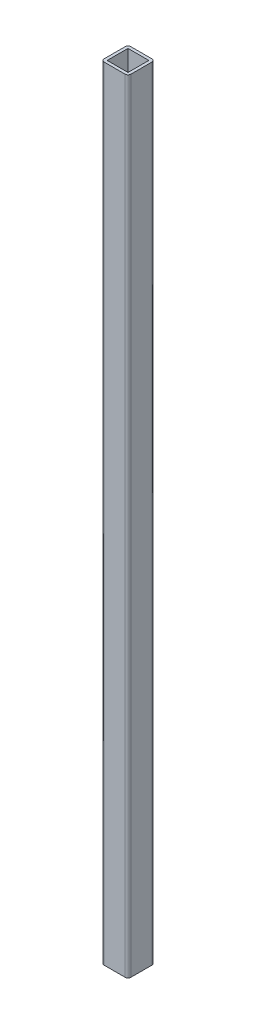
SolidWorks part; units mm, degrees
material "Plain Carbon Steel"
ref_plane "Front Plane" through (0, 0, 0) normal (0, 0, 1) x (1, 0, 0)
ref_plane "Top Plane" through (0, 0, 0) normal (0, 1, 0) x (1, 0, 0)
ref_plane "Right Plane" through (0, 0, 0) normal (1, 0, 0) x (0, 0, -1)
sketch "Sketch1" plane through (0, 0, 0) normal (0, 1, 0) x (1, 0, 0)
  line L1 (2.8, 0) -> (22.8, 0)
  line L2 (0, -2.8) -> (0, -22.8)
  line L3 (2.8, -25.6) -> (22.8, -25.6)
  line L4 (25.6, -2.8) -> (25.6, -22.8)
  arc A0 (22.8, 0) -> (25.6, -2.8) centre (22.8, -2.8) cw
  arc A1 (22.8, -25.6) -> (25.6, -22.8) centre (22.8, -22.8) ccw
  arc A2 (0, -22.8) -> (2.8, -25.6) centre (2.8, -22.8) ccw
  arc A3 (2.8, 0) -> (0, -2.8) centre (2.8, -2.8) ccw
  point P7 (25.6, 0)
  point P10 (25.6, -25.6)
  point P15 (0, 0)
  dimension "D2" = 2.8
  dimension "D1" = 25.6
extrude "Boss-Extrude1" add sketch "Sketch1" along normal blind 750.2
sketch "Sketch3" plane through (0, 0, 0) normal (0, -1, 0) x (-1, 0, 0)
  line L4 (-2.8, -2.8) -> (-22.8, -2.8)
  line L5 (-2.8, -2.8) -> (-2.8, -22.8)
  line L6 (-2.8, -22.8) -> (-22.8, -22.8)
  line L7 (-22.8, -2.8) -> (-22.8, -22.8)
  line L8 (-2.8, -2.8) -> (-22.8, -22.8) construction
  line L9 (-2.8, -22.8) -> (-22.8, -2.8) construction
  point P6 (-12.8, -12.8)
extrude "Cut-Extrude1" cut sketch "Sketch3" against normal blind 750.2
